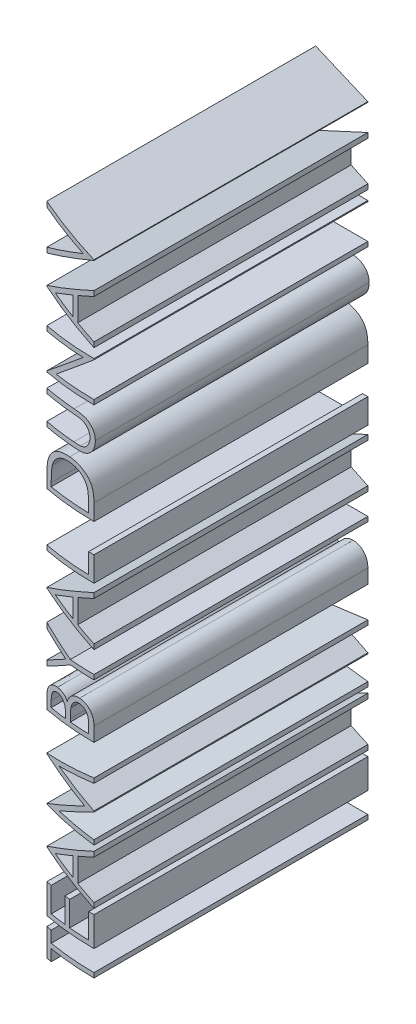
SolidWorks part; units mm, degrees
ref_plane "Front Plane" through (0, 0, 0) normal (0, 0, 1) x (1, 0, 0)
ref_plane "Top Plane" through (0, 0, 0) normal (0, 1, 0) x (1, 0, 0)
ref_plane "Right Plane" through (0, 0, 0) normal (1, 0, 0) x (0, 0, -1)
sketch "Sketch4" plane through (0, 0, 0) normal (0, 0, 1) x (1, 0, 0)
  text T0 "TEAM BYAL DUNAV" font "Century Gothic" height in points 36
extrude "Boss-Extrude4" add sketch "Sketch4" along normal blind 58
sketch "Sketch6" plane through (0, 0, 0) normal (0, 1, 0) x (1, 0, 0)
  circle A0 centre (0, 0) radius 50
  circle A1 centre (0, 0) radius 76.5321
extrude "Cut-Extrude2" cut sketch "Sketch6" along normal blind 144
